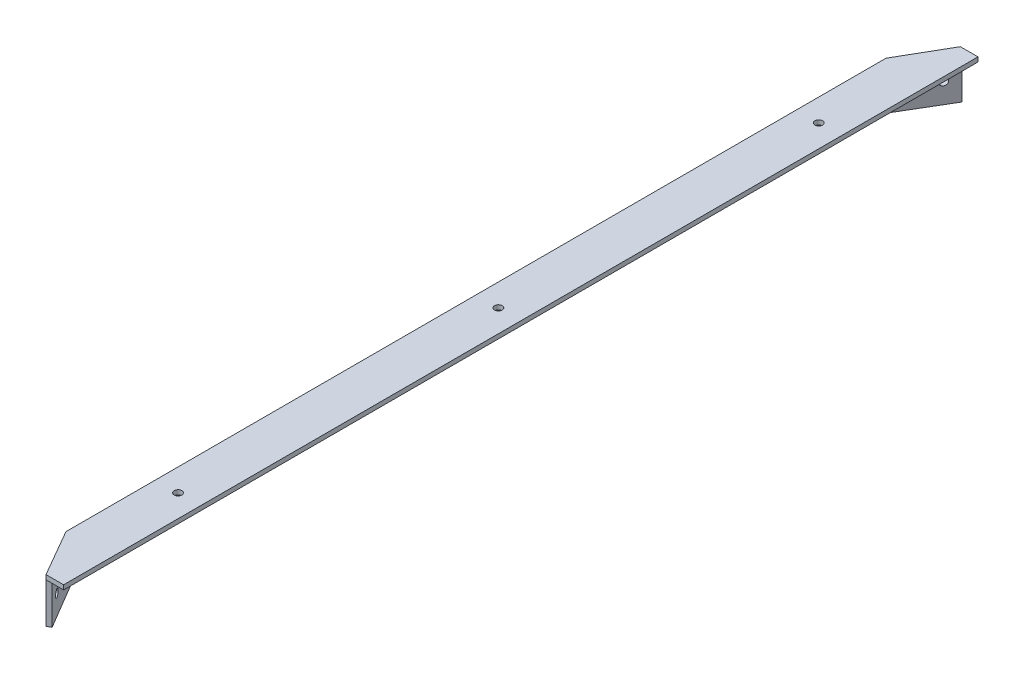
SolidWorks part; units mm, degrees
material "1.0116 (S235J2G3)"
ref_plane "Front Plane" through (0, 0, 0) normal (0, 0, 1) x (1, 0, 0)
ref_plane "Top Plane" through (0, 0, 0) normal (0, 1, 0) x (1, 0, 0)
ref_plane "Right Plane" through (0, 0, 0) normal (1, 0, 0) x (0, 0, -1)
sketch "Sketch1" plane through (0, 0, 0) normal (0, 0, 1) x (1, 0, 0)
  line L6 (0, 0) -> (0, 70)
  line L7 (0, 70) -> (70, 70)
  line L8 (70, 70) -> (70, 63)
  line L9 (70, 63) -> (7, 63)
  line L10 (7, 63) -> (7, 0)
  line L11 (7, 0) -> (0, 0)
  dimension "D1" = 70
  dimension "D2" = 70
  dimension "D3" = 7
  dimension "D4" = 7
extrude "Boss-Extrude1" add sketch "Sketch1" along normal blind 640
sketch "Sketch21" plane through (0, 0, 0) normal (0, 0, -1) x (-1, 0, 0)
  line L0 (0, 70) -> (-70, 70) construction
  line L1 (-70, 70) -> (-70, 0) construction
  line L2 (-70, 0) -> (0, 0) construction
  line L3 (0, 0) -> (0, 69.2595) construction
sketch "Sketch22" plane through (0, 70, 0) normal (0, 1, 0) x (1, 0, 0)
  line L0 (70, 0) -> (0, 0) construction
  line L1 (0, -38.5) -> (0, 38.5) construction
  circle A0 centre (35, 0) radius 6
  circle A1 centre (35, 500) radius 6
  circle A2 centre (35, -500) radius 6
  dimension "D1" = 12
  dimension "D2" = 12
  dimension "D3" = 12
  dimension "D4" = 500
  dimension "D5" = 500
  dimension "D6" = 35
  dimension "D7" = 35
extrude "Cut-Extrude4" cut sketch "Sketch22" against normal blind 10
sketch "Sketch23" plane through (0, 0, 0) normal (0, 1, 0) x (1, 0, 0)
  line L0 (0, -640) -> (42.5, -713.6122)
  line L1 (42.5, -713.6122) -> (48.5622, -710.1122)
  line L2 (48.5622, -710.1122) -> (7, -640)
  line L3 (7, -640) -> (0, -640)
  line L4 (0, -38.5) -> (0, 38.5) construction
  dimension "D1" = 7
  dimension "D2" = 210
  dimension "D3" = 85
extrude "Boss-Extrude2" add sketch "Sketch23" along normal blind 63
sketch "Sketch25" plane through (0, 63, 0) normal (0, 1, 0) x (1, 0, 0)
  line L0 (70, -640) -> (0, -640)
  line L1 (70, -640) -> (70, 0) construction
  line L2 (7, -640) -> (70, -640) construction
  line L3 (0, -640) -> (42.5, -713.6122) construction
  line L4 (0, -640) -> (42.5, -713.6122)
  line L5 (42.5, -713.6122) -> (48.5622, -710.1122) construction
  line L6 (42.5, -713.6122) -> (70, -713.6122)
  line L7 (70, -713.6122) -> (70, -640)
extrude "Boss-Extrude3" add sketch "Sketch25" along normal blind 7
sketch "Sketch26" plane through (-275.5567, 0, 163.3488) normal (0.8602, 0, -0.5099) x (-0.5099, 0, -0.8602)
  line L0 (-635.6125, 0) -> (-554.1071, 0) construction
  line L1 (-635.6125, 63) -> (-635.6125, 0) construction
  line L2 (-554.1071, 0) -> (-554.1071, 63) construction
  circle A0 centre (-614.3625, 31.5) radius 6
  circle A1 centre (-575.3571, 31.5) radius 6
  dimension "D1" = 12
  dimension "D2" = 12
  dimension "D3" = 31.5
  dimension "D4" = 31.5
  dimension "D5" = 21.25
  dimension "D6" = 21.25
extrude "Cut-Extrude5" cut sketch "Sketch26" against normal blind 7
mirror "Mirror1" about plane through (0, 0, 0) normal (0, 0, 1) of bodies 114 116
